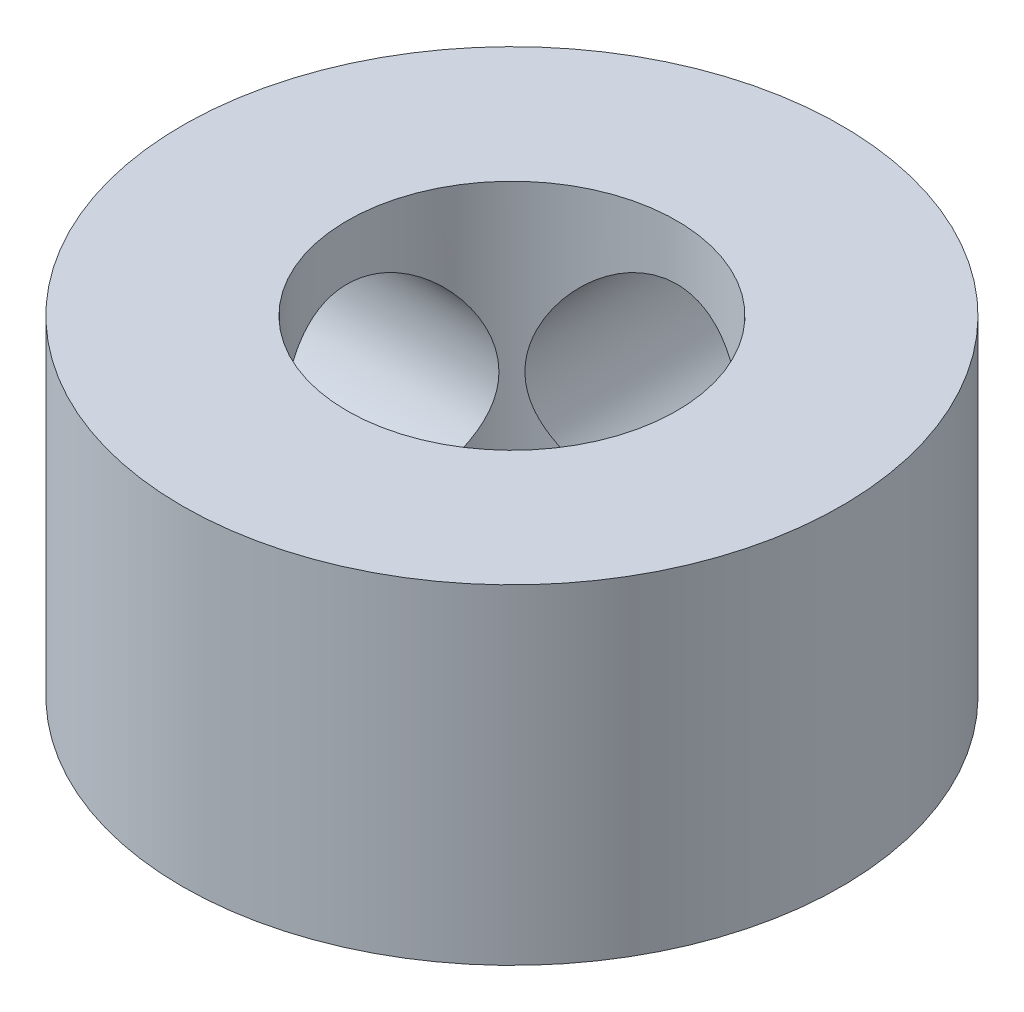
SolidWorks part; units mm, degrees
material "普通碳钢"
ref_plane "前视基准面" through (0, 0, 0) normal (0, 0, 1) x (1, 0, 0)
ref_plane "上视基准面" through (0, 0, 0) normal (0, 1, 0) x (1, 0, 0)
ref_plane "右视基准面" through (0, 0, 0) normal (1, 0, 0) x (0, 0, -1)
other "Configuration Table"
sketch "草图1" plane through (0, 0, 0) normal (0, 1, 0) x (1, 0, 0)
  circle A0 centre (0, 0) radius 3
  circle A1 centre (0, 0) radius 6
  dimension "D1" = 6
  dimension "D2" = 12
extrude "凸台-拉伸1" add sketch "草图1" along normal blind 6
sketch "草图2" plane through (0, 0, 0) normal (0, 0, 1) x (1, 0, 0)
  line L0 (0, 6) -> (0, 0) construction
  line L1 (3, 6) -> (-3, 6) construction
  circle A0 centre (0, 3) radius 2
  dimension "D1" = 4
extrude "切除-拉伸1" cut sketch "草图2" against normal blind 10
sketch "草图3" plane through (0, 0, 0) normal (1, 0, 0) x (0, 0, -1)
  line L0 (0, 6) -> (0, 0) construction
  line L1 (3, 6) -> (-3, 6) construction
  circle A0 centre (0, 3) radius 2
  dimension "D1" = 4
extrude "切除-拉伸2" cut sketch "草图3" against normal blind 10
